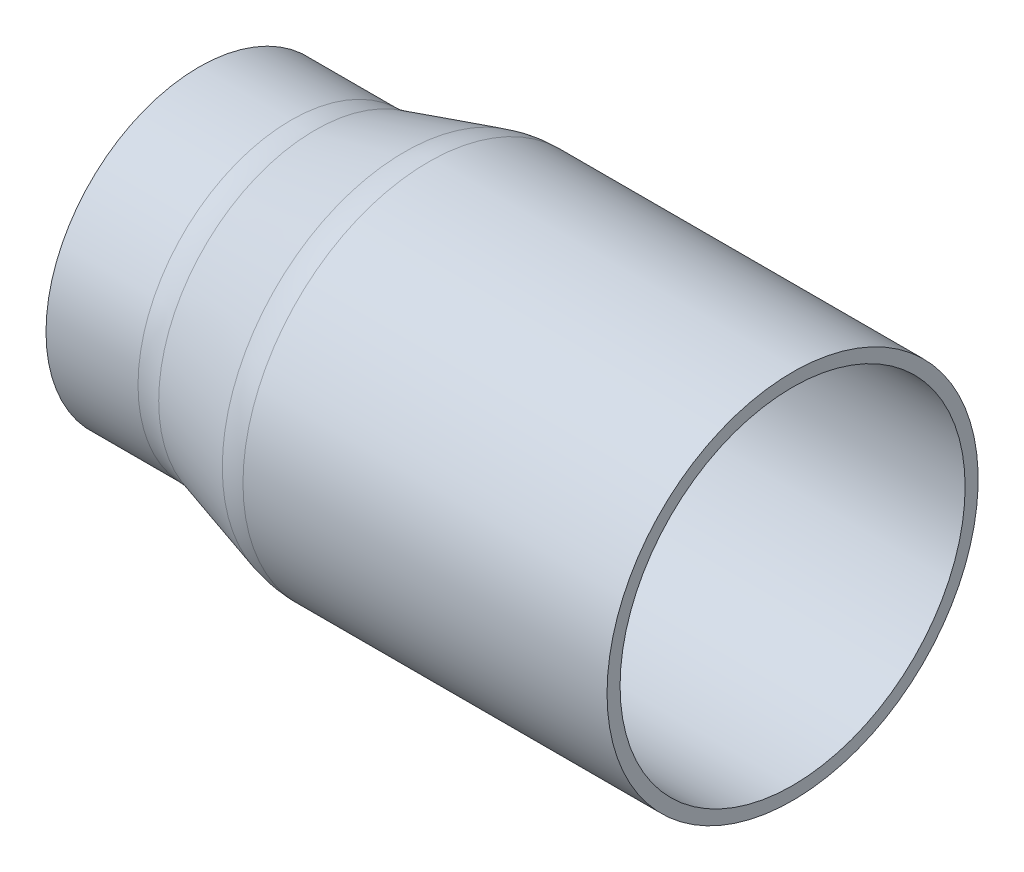
SolidWorks part; units mm, degrees
ref_plane "Front Plane" through (0, 0, 0) normal (0, 0, 1) x (1, 0, 0)
ref_plane "Top Plane" through (0, 0, 0) normal (0, 1, 0) x (1, 0, 0)
ref_plane "Right Plane" through (0, 0, 0) normal (1, 0, 0) x (0, 0, -1)
sketch "Sketch1" plane through (0, 0, 0) normal (0, 1, 0) x (1, 0, 0)
  line L0 (-73.7294, 0) -> (86.0313, 0) construction
  line L1 (-64.453, 16.1) -> (-53.8665, 16.1)
  line L2 (-64.453, 17.6) -> (-53.8665, 17.6)
  line L3 (-51.0949, 17.9918) -> (-40.8111, 20.9582)
  line L4 (-51.0949, 16.4918) -> (-40.8111, 19.4582)
  line L5 (-38.0395, 21.35) -> (3.847, 21.35)
  line L6 (3.847, 21.35) -> (3.847, 19.85)
  line L7 (3.847, 19.85) -> (-38.0395, 19.85)
  line L8 (-64.453, 17.6) -> (-64.453, 16.1)
  arc A2 (-53.8665, 17.6) -> (-51.0949, 17.9918) centre (-53.8665, 27.6) ccw
  arc A3 (-53.8665, 16.1) -> (-51.0949, 16.4918) centre (-53.8665, 26.1) ccw
  arc A4 (-40.8111, 20.9582) -> (-38.0395, 21.35) centre (-38.0395, 11.35) cw
  arc A5 (-40.8111, 19.4582) -> (-38.0395, 19.85) centre (-38.0395, 9.85) cw
  point P10 (3.847, 20.6)
  point P15 (-52.453, 17.6)
  point P18 (-52.453, 16.1)
  point P21 (-39.453, 21.35)
  point P24 (-39.453, 19.85)
  dimension "D1" = 16.1
  dimension "D2" = 17.6
  dimension "D9" = 10
  dimension "D3" = 12
  dimension "D4" = 12
  dimension "D5" = 21.35
  dimension "D6" = 25
  dimension "D7" = 1.5
  dimension "D8" = 68.3
revolve "Revolve1" add sketch "Sketch1" angle 360 about L0
